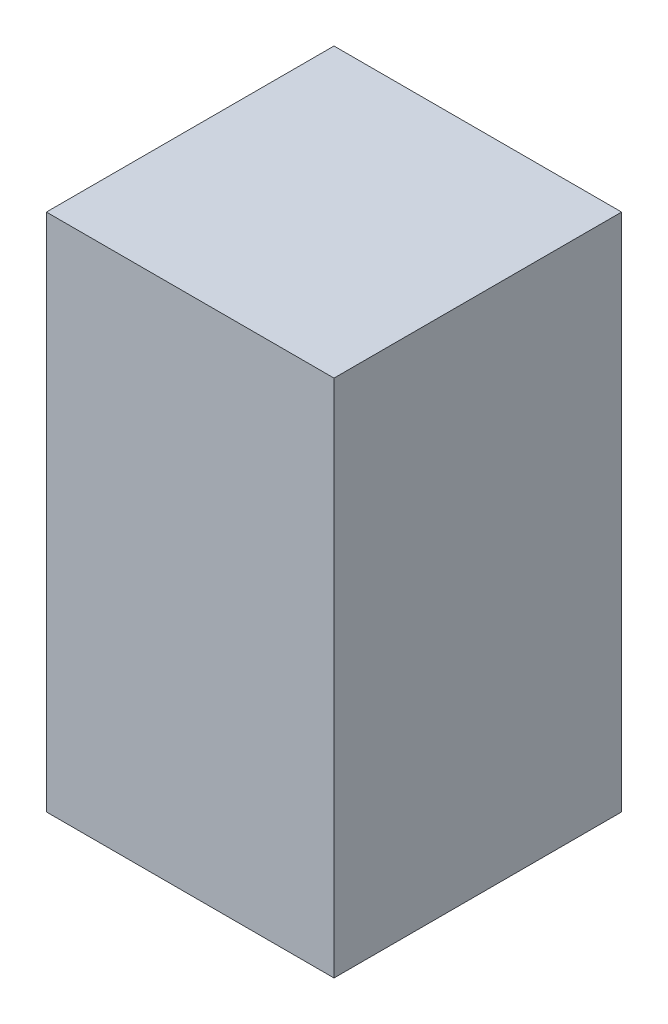
SolidWorks part; units mm, degrees
ref_plane "Alzado" through (0, 0, 0) normal (0, 0, 1) x (1, 0, 0)
ref_plane "Planta" through (0, 0, 0) normal (0, 1, 0) x (1, 0, 0)
ref_plane "Vista lateral" through (0, 0, 0) normal (1, 0, 0) x (0, 0, -1)
sketch "Croquis1" plane through (0, 0, 0) normal (0, 0, 1) x (1, 0, 0)
  line L0 (0, 0) -> (0, -550) construction
  line L1 (0, 0) -> (600, 0)
  line L2 (0, 0) -> (0, -1100)
  line L3 (0, -1100) -> (600, -1100)
  line L4 (600, 0) -> (600, -1100)
  line L5 (300, -550) -> (600, -550) construction
  line L11 (-10, 10) -> (610, 10)
  line L12 (-10, 10) -> (-10, -1110)
  line L13 (-10, -1110) -> (610, -1110)
  line L14 (610, 10) -> (610, -1110)
  line L15 (-10, 10) -> (610, -1110) construction
  line L16 (-10, -1110) -> (610, 10) construction
  dimension "D1" = 300
  dimension "D2" = 600
  dimension "D3" = 1100
extrude "Saliente-Extruir1" add sketch "Croquis1" along normal blind 600
sketch "Croquis6" plane through (0, 0, 600) normal (0, 0, 1) x (1, 0, 0)
  line L1 (-10, 10) -> (610, 10)
  line L2 (-10, 10) -> (-10, -1110)
  line L3 (-10, -1110) -> (610, -1110)
  line L4 (610, 10) -> (610, -1110)
extrude "Saliente-Extruir4" add sketch "Croquis6" along normal blind 20
